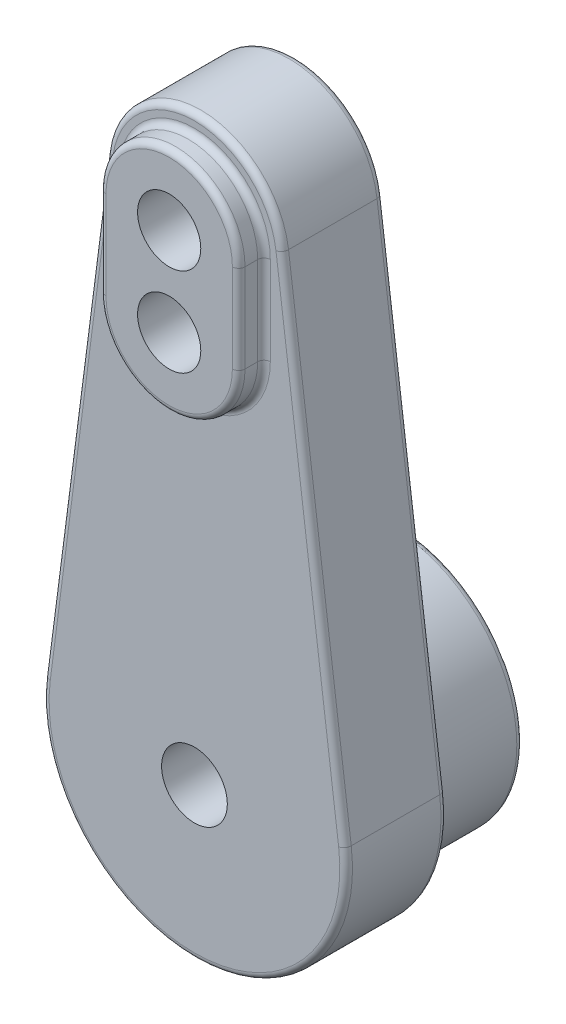
SolidWorks part; units mm, degrees
ref_plane "Front Plane" through (0, 0, 0) normal (0, 0, 1) x (1, 0, 0)
ref_plane "Top Plane" through (0, 0, 0) normal (0, 1, 0) x (1, 0, 0)
ref_plane "Right Plane" through (0, 0, 0) normal (1, 0, 0) x (0, 0, -1)
sketch "Sketch1" plane through (0, 0, 0) normal (0, 0, 1) x (1, 0, 0)
  line L0 (0, 0) -> (0, 19.5) construction
  line L1 (-3.4711, 19.9487) -> (-5.9505, 0.7692)
  line L2 (3.4711, 19.9487) -> (5.9505, 0.7692)
  arc A0 (-5.9505, 0.7692) -> (5.9505, 0.7692) centre (0, 0) ccw
  arc A1 (3.4711, 19.9487) -> (-3.4711, 19.9487) centre (0, 19.5) ccw
  circle A2 centre (0, 0) radius 1.3
  dimension "D1" = 7
  dimension "D3" = 12
  dimension "D4" = 2.6
  dimension "D2" = 19.5
extrude "Boss-Extrude1" add sketch "Sketch1" against normal blind 4
sketch "Sketch2" plane through (0, 0, 0) normal (0, 0, 1) x (1, 0, 0)
  line L0 (0, 19.5) -> (0, 16) construction
  line L1 (-2.75, 19.5) -> (-2.75, 16)
  line L2 (2.75, 19.5) -> (2.75, 16)
  arc A0 (-2.75, 19.5) -> (2.75, 19.5) centre (0, 19.5) cw
  arc A1 (-2.75, 16) -> (2.75, 16) centre (0, 16) ccw
  dimension "D1" = 3.5
  dimension "D2" = 2.75
  dimension "D3" = 2.75
extrude "Boss-Extrude2" add sketch "Sketch2" along normal blind 1
sketch "Sketch3" plane through (0, 0, -4) normal (0, 0, -1) x (-1, 0, 0)
  circle A0 centre (0, 0) radius 5
  circle A1 centre (0, 0) radius 3
  dimension "D1" = 10
  dimension "D2" = 6
extrude "Boss-Extrude3" add sketch "Sketch3" along normal blind 4
sketch "Sketch4" plane through (0, 0, 1) normal (0, 0, 1) x (1, 0, 0)
  circle A0 centre (0, 19.5) radius 1.25
  circle A1 centre (0, 16) radius 1.25
  dimension "D1" = 2.5
extrude "Cut-Extrude1" cut sketch "Sketch4" against normal blind 5
fillet "Fillet1" radius 0.25 18 edges at (0, 13.25, 1) (-2.75, 17.75, 1) (0, 22.25, 1) (2.75, 17.75, 1) (-4.7108, 10.359, 0) (0, -6, 0) (4.7108, 10.359, 0) (0, 23, 0) (-4.7108, 10.359, -4) (0, 23, -4) (4.7108, 10.359, -4) (0, -6, -4) (5, 0, -4) (-5, 0, -8) (0, 13.25, 0) (-2.75, 17.75, 0) (0, 22.25, 0) (2.75, 17.75, 0)
